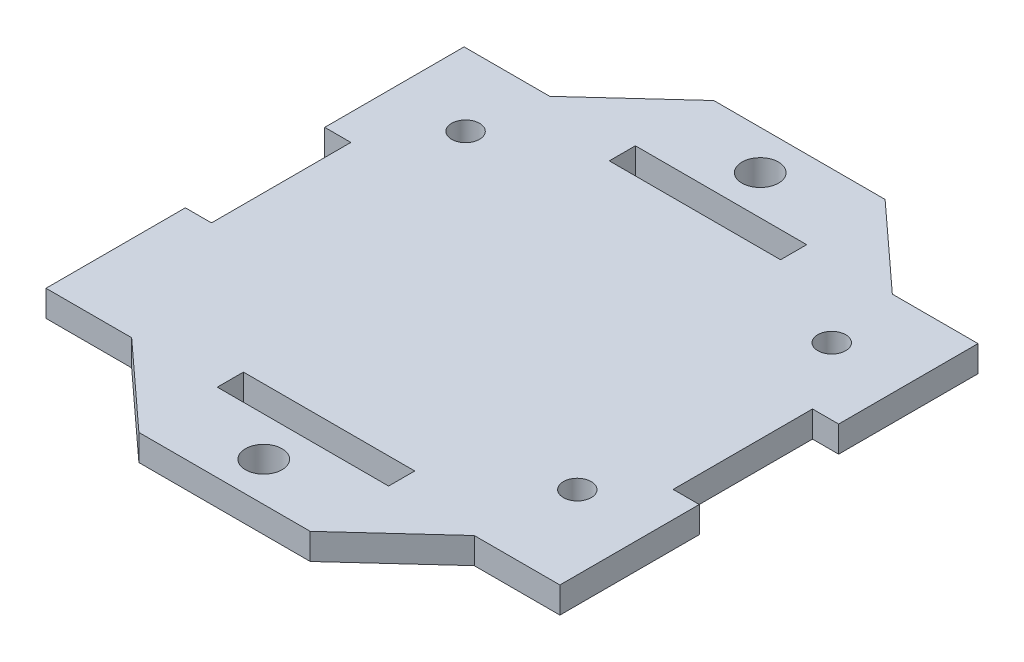
SolidWorks part; units mm, degrees
ref_plane "Front Plane" through (0, 0, 0) normal (0, 0, 1) x (1, 0, 0)
ref_plane "Top Plane" through (0, 0, 0) normal (0, 1, 0) x (1, 0, 0)
ref_plane "Right Plane" through (0, 0, 0) normal (1, 0, 0) x (0, 0, -1)
sketch "Sketch1" plane through (0, 0, 0) normal (0, 1, 0) x (1, 0, 0)
  line L0 (-29.5, 24) -> (-29.5, 8)
  line L1 (-25, -19.5) -> (25, -19.5) construction
  line L2 (-25, -19.5) -> (-25, 19.5) construction
  line L3 (-25, 19.5) -> (25, 19.5) construction
  line L4 (25, -19.5) -> (25, 19.5) construction
  line L5 (-25, -19.5) -> (25, 19.5) construction
  line L6 (-25, 19.5) -> (25, -19.5) construction
  line L11 (-29.5, 8) -> (-26.5, 8)
  line L12 (-26.5, 8) -> (-26.5, -8)
  line L13 (-26.5, -8) -> (-29.5, -8)
  line L14 (-29.5, -8) -> (-29.5, -24)
  line L15 (-29.5, -24) -> (-9.8333, -24)
  line L16 (-9.8333, -24) -> (-9.8333, -21)
  line L17 (-9.8333, -21) -> (9.8333, -21)
  line L18 (9.8333, -21) -> (9.8333, -24)
  line L19 (9.8333, -24) -> (29.5, -24)
  line L20 (-21.0185, 15.69) -> (0, 0) construction
  line L21 (29.5, -24) -> (29.5, -8)
  line L22 (29.5, -8) -> (26.5, -8)
  line L23 (26.5, -8) -> (26.5, 8)
  line L24 (26.5, 8) -> (29.5, 8)
  line L25 (29.5, 8) -> (29.5, 24)
  line L26 (29.5, 24) -> (9.8333, 24)
  line L27 (9.8333, 24) -> (9.8333, 21)
  line L28 (9.8333, 21) -> (-9.8333, 21)
  line L29 (-9.8333, 21) -> (-9.8333, 24)
  line L30 (-9.8333, 24) -> (-29.5, 24)
  line L31 (0, 0) -> (21.0185, 15.69) construction
  circle A0 centre (-21.0185, 15.69) radius 1.6
  circle A1 centre (21.0185, 15.69) radius 1.6
  circle A2 centre (21.0185, -13.52) radius 1.6
  point P0 (0, 0)
  point P6 (0, 0)
  point P23 (-26.5, 0)
  point P26 (0, -21)
  dimension "D8" = 3.2
  dimension "D1" = 50
  dimension "D2" = 39
  dimension "D3" = 3
  dimension "D4" = 4.5
  dimension "D5" = 4.5
  dimension "D7" = 42.037
  dimension "D9" = 3.81
  dimension "D10" = 29.21
  dimension "D6" = 2
extrude "Boss-Extrude1" add sketch "Sketch1" along normal blind 3
sketch "Sketch2" plane through (0, 3, 0) normal (0, 1, 0) x (1, 0, 0)
  line L0 (-19.6667, 24) -> (-9.8333, 33)
  line L1 (-9.8333, 24) -> (-29.5, 24) construction
  line L2 (-9.8333, 33) -> (9.8333, 33)
  line L3 (9.8333, 33) -> (19.6667, 24)
  line L4 (29.5, 24) -> (9.8333, 24) construction
  line L6 (-19.6667, 24) -> (19.6667, 24)
  line L7 (-9.8333, 24) -> (9.8333, 33) construction
  circle A0 centre (0, 28.5) radius 2.1
  point P13 (19.6667, 24)
  point P16 (0, 28.5)
  dimension "D1" = 4.2
  dimension "D2" = 9
extrude "Boss-Extrude2" add sketch "Sketch2" against normal blind 3
mirror "Mirror1" about plane through (0, 0, 0) normal (0, 0, 1) of "Boss-Extrude2"
